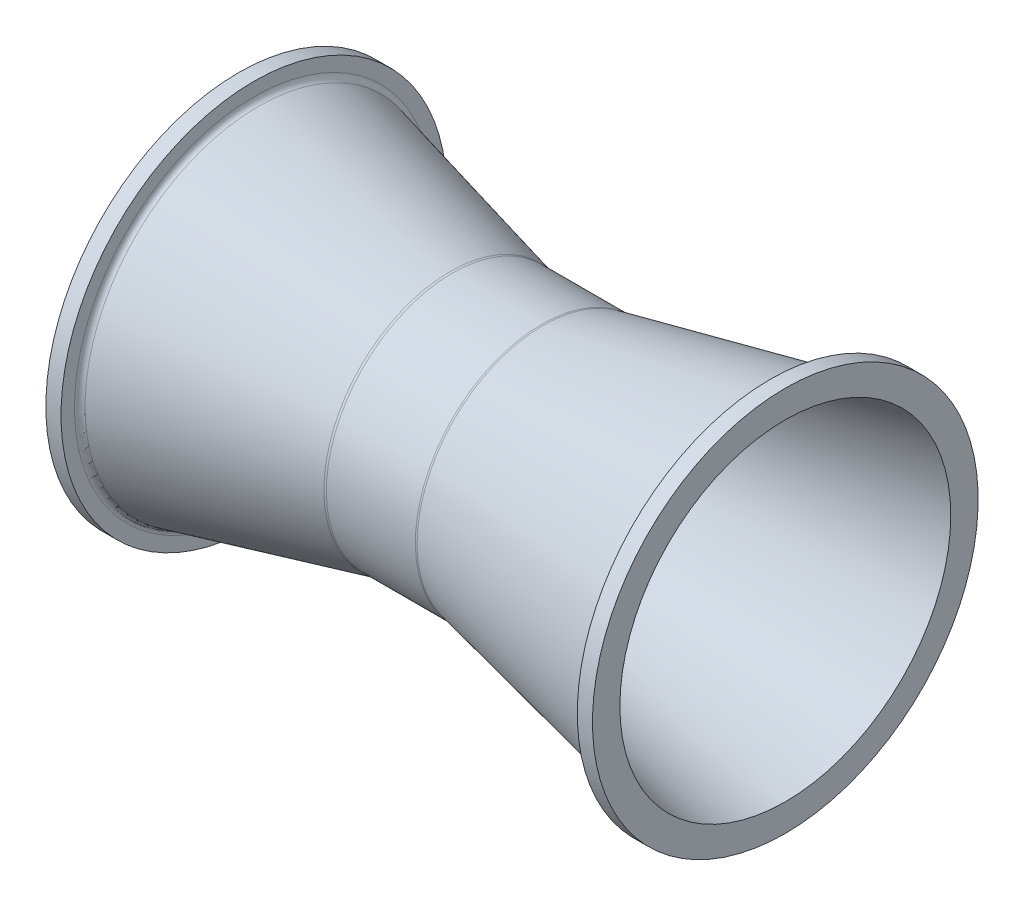
SolidWorks part; units mm, degrees
material "6061-T6 (SS)"
ref_plane "Front Plane" through (0, 0, 0) normal (0, 0, 1) x (1, 0, 0)
ref_plane "Top Plane" through (0, 0, 0) normal (0, 1, 0) x (1, 0, 0)
ref_plane "Right Plane" through (0, 0, 0) normal (1, 0, 0) x (0, 0, -1)
sketch "Sketch1" plane through (0, 0, 0) normal (1, 0, 0) x (0, 0, -1)
  circle A0 centre (0, 0) radius 37.5
  circle A1 centre (0, 0) radius 29 construction
  circle A2 centre (29, 0) radius 4
  circle A3 centre (-14.5, -25.1147) radius 4
  circle A4 centre (-14.5, 25.1147) radius 4
  circle A5 centre (0, 0) radius 15
  point P13 (0, 0)
  dimension "D1" = 75
  dimension "D2" = 58
  dimension "D3" = 8
  dimension "D5" = 14.5
  dimension "D6" = 25.1147
  dimension "D7" = 30
  dimension "D4" = 3
extrude "Boss-Extrude1" add sketch "Sketch1" along normal blind 6
sketch "Sketch2" plane through (0, 0, 0) normal (0, 0, 1) x (1, 0, 0)
  line L0 (0, 0) -> (-70, 0) construction
  line L1 (0, 0) -> (110, 0) construction
  line L2 (-70, 63.5) -> (-70, 0) construction
  line L3 (110, 63.5) -> (110, 0) construction
  line L4 (-70, 63.5) -> (-65, 63.5)
  line L5 (-65, 63.5) -> (-65, 57.5)
  line L8 (110, 63.5) -> (105, 63.5)
  line L9 (105, 63.5) -> (105, 57.5)
  line L12 (0, 37.5) -> (0, 41.5) construction
  line L13 (-65, 57.5) -> (0, 41.5)
  line L14 (0, 41.5) -> (30, 41.5)
  line L15 (30, 41.5) -> (105, 57.5)
  line L16 (0, 37.5) -> (-70, 54.7308)
  line L19 (-70, 63.5) -> (-70, 54.7308)
  line L20 (-0.4851, 37.5) -> (30.4219, 37.5)
  line L21 (30.4219, 37.5) -> (110, 54.4767)
  line L22 (110, 63.5) -> (110, 54.4767)
  line L25 (-66, 53.6268) -> (-66, 0) construction
  line L26 (-66, 53.6268) -> (-0.4851, 37.5) construction
  line L28 (106, 53.6233) -> (106, 0) construction
  line L29 (30.4219, 37.5) -> (106, 53.6233) construction
  line L30 (106, 53.6233) -> (106, 53.6233) construction
  line L31 (106, 53.6233) -> (106, 53.6233) construction
  line L32 (-66, 53.6268) -> (-66, 53.6268) construction
  line L33 (-66, 53.6268) -> (-66, 53.6268) construction
  point P8 (-70, 0)
  point P11 (110, 0)
  dimension "D1" = 70
  dimension "D2" = 180
  dimension "D3" = 63.5
  dimension "D4" = 5
  dimension "D5" = 6
  dimension "D6" = 4
  dimension "D7" = 30
  dimension "D8" = 4
revolve "Revolve1" add sketch "Sketch2" angle 360 about L0
fillet "Fillet1" radius 2 2 edges at (105, 57.5, 0) (-65, 57.5, 0)
fillet "Fillet2" radius 3 2 edges at (30, 41.5, 0) (0, 41.5, 0)
sketch "Sketch3" plane through (0, 0, 0) normal (0, 0, 1) x (1, 0, 0)
  line L0 (-70, 78.7208) -> (-70, 114.7)
  line L1 (0, 0) -> (-70, 0) construction
  line L2 (-70, 63.5) -> (-70, -63.5) construction
  line L3 (-45, 139.7) -> (85, 139.7)
  line L4 (0, 0) -> (110, 0) construction
  line L5 (110, -63.5) -> (110, 63.5) construction
  line L6 (110, 114.7) -> (110, 78.7208)
  line L7 (-65, 63.5) -> (-65, 59.0674)
  line L8 (-65, 63.5) -> (-66.3449, 65.7056)
  line L9 (-70, 0) -> (-70, 71.7) construction
  line L11 (20, 139.7) -> (20, 53.3218) construction
  line L12 (105, 63.5) -> (105, 59.0674)
  line L13 (105, 63.5) -> (106.3449, 65.7056)
  line L14 (110, 78.7208) -> (110, 0) construction
  line L15 (-61, 64.6233) -> (-61, 59.0674)
  line L16 (-61, 64.6233) -> (-62.9297, 67.7881)
  line L17 (-66, 78.7208) -> (-66, 114.7)
  line L18 (-45, 135.7) -> (85, 135.7)
  line L19 (106, 114.7) -> (106, 78.7208)
  line L20 (101, 64.6233) -> (102.9297, 67.7881)
  line L21 (101, 64.6233) -> (101, 59.0674)
  line L22 (-65, 59.0674) -> (-61, 59.0674)
  line L23 (101, 59.0674) -> (105, 59.0674)
  arc A0 (-66.3449, 65.7056) -> (-70, 78.7208) centre (-45, 78.7208) cw
  arc A1 (-70, 114.7) -> (-45, 139.7) centre (-45, 114.7) cw
  arc A2 (85, 139.7) -> (110, 114.7) centre (85, 114.7) cw
  arc A3 (106.3449, 65.7056) -> (110, 78.7208) centre (85, 78.7208) ccw
  arc A4 (-62.9297, 67.7881) -> (-66, 78.7208) centre (-45, 78.7208) cw
  arc A5 (-66, 114.7) -> (-45, 135.7) centre (-45, 114.7) cw
  arc A6 (85, 135.7) -> (106, 114.7) centre (85, 114.7) cw
  arc A7 (102.9297, 67.7881) -> (106, 78.7208) centre (85, 78.7208) ccw
  point P21 (-70, 139.7)
  dimension "D4" = 25
  dimension "D5" = 25
  dimension "D6" = 25
  dimension "D1" = 139.7
  dimension "D2" = 68
  dimension "D3" = 9.6042
  dimension "D7" = 4
